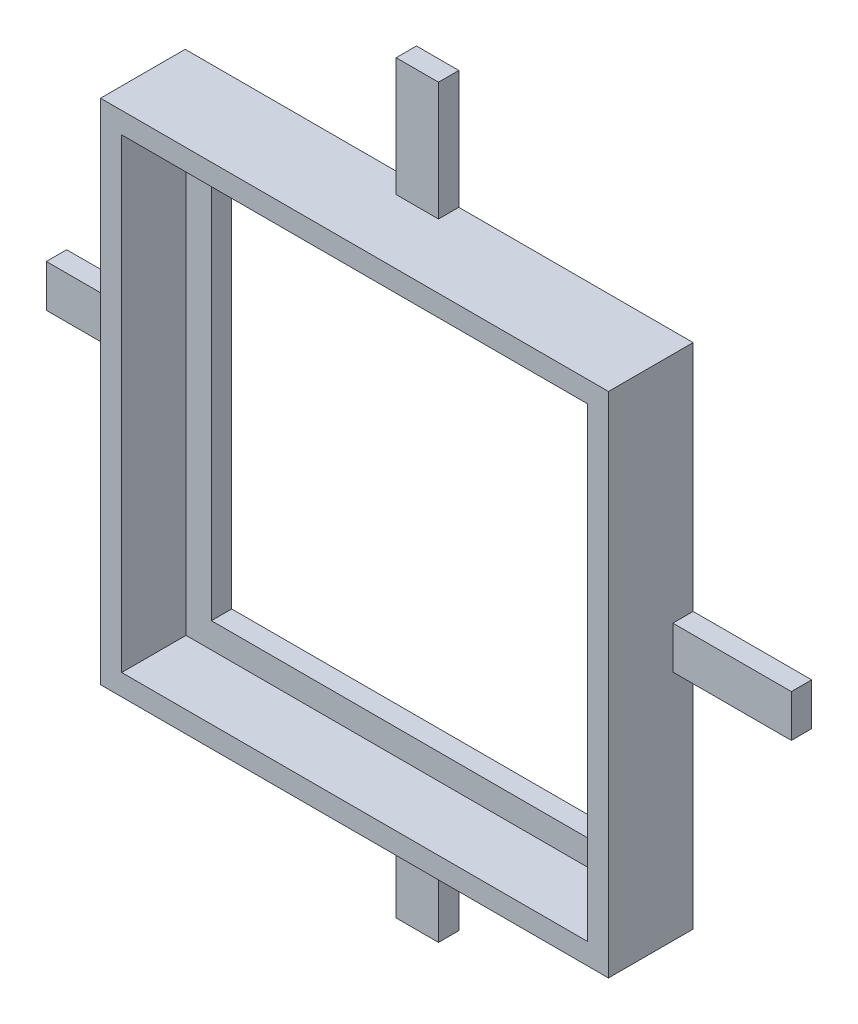
SolidWorks part; units mm, degrees
ref_plane "Plan de face" through (0, 0, 0) normal (0, 0, 1) x (1, 0, 0)
ref_plane "Plan de dessus" through (0, 0, 0) normal (0, 1, 0) x (1, 0, 0)
ref_plane "Plan de droite" through (0, 0, 0) normal (1, 0, 0) x (0, 0, -1)
sketch "Esquisse1" plane through (0, 0, 0) normal (0, 0, 1) x (1, 0, 0)
  line L1 (-150, 150) -> (150, 150)
  line L2 (-150, 150) -> (-150, -150)
  line L3 (-150, -150) -> (150, -150)
  line L4 (150, 150) -> (150, -150)
  line L5 (-150, 150) -> (150, -150) construction
  line L6 (-150, -150) -> (150, 150) construction
  line L7 (-137.5, 137.5) -> (137.5, 137.5)
  line L8 (-137.5, 137.5) -> (-137.5, -137.5)
  line L9 (-137.5, -137.5) -> (137.5, -137.5)
  line L10 (137.5, 137.5) -> (137.5, -137.5)
  line L11 (-137.5, 137.5) -> (137.5, -137.5) construction
  line L12 (-137.5, -137.5) -> (137.5, 137.5) construction
  point P0 (0, 0)
  point P6 (0, 0)
  dimension "D1" = 300
  dimension "D2" = 300
  dimension "D3" = 275
  dimension "D4" = 275
extrude "Boss.-Extru.1" add sketch "Esquisse1" along normal blind 50
sketch "Esquisse2" plane through (0, 0, 0) normal (0, 0, 1) x (1, 0, 0)
  line L1 (-137.5, 137.5) -> (137.5, 137.5)
  line L2 (-137.5, 137.5) -> (-137.5, -137.5)
  line L3 (-137.5, -137.5) -> (137.5, -137.5)
  line L4 (137.5, 137.5) -> (137.5, -137.5)
  line L5 (-137.5, 137.5) -> (137.5, -137.5) construction
  line L6 (-137.5, -137.5) -> (137.5, 137.5) construction
  line L7 (-122.5, 122.5) -> (122.5, 122.5)
  line L8 (-122.5, 122.5) -> (-122.5, -122.5)
  line L9 (-122.5, -122.5) -> (122.5, -122.5)
  line L10 (122.5, 122.5) -> (122.5, -122.5)
  line L11 (-122.5, 122.5) -> (122.5, -122.5) construction
  line L12 (-122.5, -122.5) -> (122.5, 122.5) construction
  point P0 (0, 0)
  point P7 (0, 0)
  dimension "D1" = 245
  dimension "D2" = 245
extrude "Boss.-Extru.2" add sketch "Esquisse2" along normal blind 12 contours L2 L1 L4 L3 | L8 L7 L10 L9
sketch "Esquisse3" plane through (0, 0, 0) normal (0, 0, 1) x (1, 0, 0)
  line L0 (-13.3902, -220) -> (0, -150) construction
  line L1 (150, 150) -> (-150, 150) construction
  line L3 (-13.3902, 150) -> (-13.3902, 220)
  line L4 (-13.3902, 220) -> (11.6098, 220)
  line L5 (11.6098, 150) -> (11.6098, 220)
  line L6 (0, 150) -> (11.6098, 220) construction
  line L7 (-13.3902, 220) -> (0, 150) construction
  line L8 (-13.3902, 150) -> (11.6098, 150)
  line L9 (0, 0) -> (150, 0) construction
  line L10 (150, -150) -> (150, 150) construction
  line L11 (0, 0) -> (0, 150) construction
  line L12 (150, -12.5) -> (150, 12.5)
  line L13 (150, 12.5) -> (220, 12.5)
  line L15 (150, -12.5) -> (220, -12.5)
  line L16 (220, 12.5) -> (220, -12.5)
  line L17 (150, 0) -> (220, -12.5) construction
  line L18 (150, 0) -> (220, 12.5) construction
  line L19 (-150, 0) -> (-220, 12.5) construction
  line L20 (-150, 0) -> (-220, -12.5) construction
  line L21 (-150, -12.5) -> (-220, -12.5)
  line L22 (-150, 12.5) -> (-220, 12.5)
  line L23 (-150, -12.5) -> (-150, 12.5)
  line L24 (-220, 12.5) -> (-220, -12.5)
  line L25 (0, -150) -> (11.6098, -220) construction
  line L26 (-13.3902, -150) -> (11.6098, -150)
  line L27 (11.6098, -150) -> (11.6098, -220)
  line L28 (-13.3902, -220) -> (11.6098, -220)
  line L29 (-13.3902, -150) -> (-13.3902, -220)
  point P3 (0, 150)
  point P27 (0, -150)
  dimension "D1" = 70
  dimension "D2" = 25
  dimension "D3" = 70
  dimension "D4" = 25
extrude "Boss.-Extru.3" add sketch "Esquisse3" along normal blind 12
